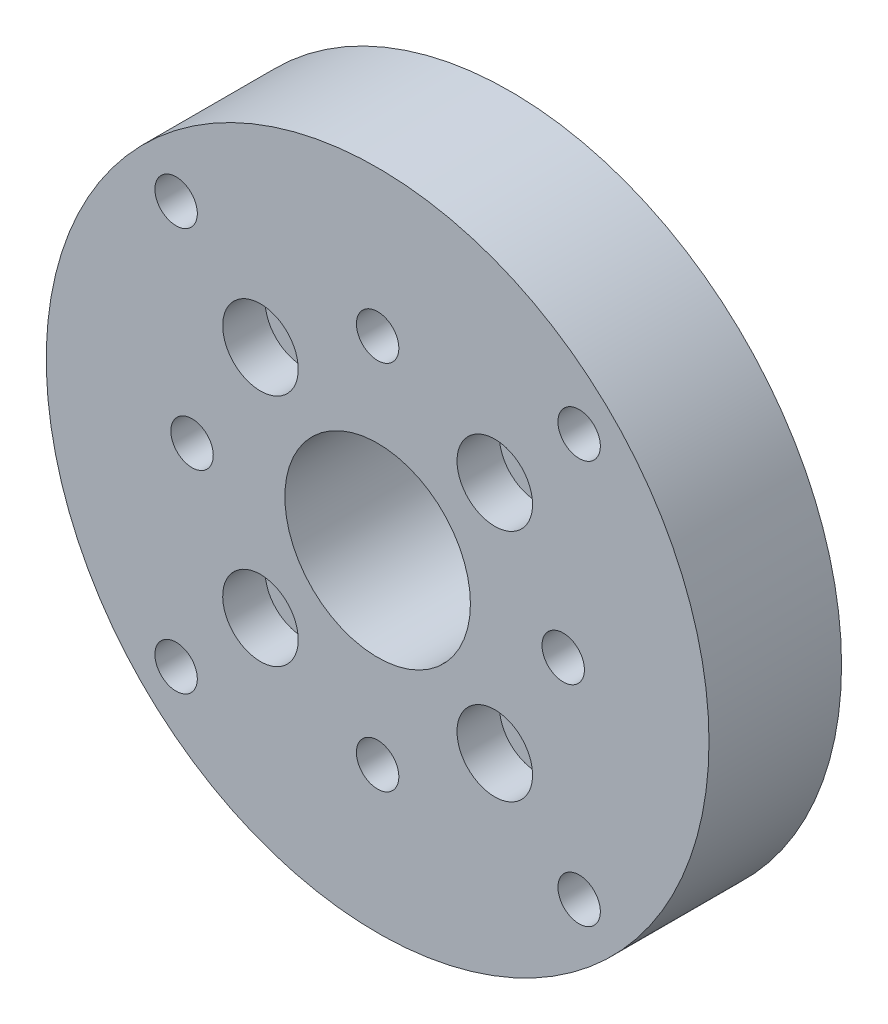
SolidWorks part; units mm, degrees
ref_plane "Front Plane" through (0, 0, 0) normal (0, 0, 1) x (1, 0, 0)
ref_plane "Top Plane" through (0, 0, 0) normal (0, 1, 0) x (1, 0, 0)
ref_plane "Right Plane" through (0, 0, 0) normal (1, 0, 0) x (0, 0, -1)
sketch "Sketch1" plane through (0, 0, 0) normal (0, 0, 1) x (1, 0, 0)
  circle A0 centre (0, 0) radius 25
  dimension "D1" = 50
extrude "Boss-Extrude1" add sketch "Sketch1" along normal blind 10
sketch "Sketch2" plane through (0, 0, 10) normal (0, 0, 1) x (1, 0, 0)
  line L0 (-8.8388, 8.8388) -> (0, 0) construction
  line L1 (0, 0) -> (0, 12.5) construction
  circle A0 centre (0, 0) radius 12.5 construction
  circle A1 centre (-8.8388, 8.8388) radius 1.6
  dimension "D1" = 25
  dimension "D2" = 3.2
  dimension "D3" = 45
extrude "Cut-Extrude1" cut sketch "Sketch2" against normal through all
sketch "Sketch5" plane through (0, 0, 10) normal (0, 0, 1) x (1, 0, 0)
  circle A0 centre (-8.8388, 8.8388) radius 1.6 construction
  circle A1 centre (-8.8388, 8.8388) radius 1.6 construction
  circle A2 centre (-8.8388, 8.8388) radius 2.85
  dimension "D1" = 5.7
extrude "Cut-Extrude4" cut sketch "Sketch5" against normal blind 3.2
pattern_circular "CirPattern1" count 4 over 360 about axis through (0, 0, 0) along (0, 0, 1) of "Cut-Extrude1", "Cut-Extrude4"
sketch "Sketch8" plane through (0, 0, 0) normal (0, 0, -1) x (-1, 0, 0)
  circle A0 centre (0, 0) radius 14 construction
  circle A1 centre (0, 14) radius 1.6
  dimension "D1" = 28
  dimension "D2" = 3.2
extrude "Cut-Extrude6" cut sketch "Sketch8" against normal through all
sketch "Sketch3" plane through (0, 0, 0) normal (0, 0, 1) x (1, 0, 0)
  line L1 (2.85, 12.3546) -> (2.85, 15.6454)
  line L2 (2.85, 15.6454) -> (0, 17.2909)
  line L3 (0, 17.2909) -> (-2.85, 15.6454)
  line L4 (-2.85, 15.6454) -> (-2.85, 12.3546)
  line L5 (-2.85, 12.3546) -> (0, 10.7091)
  line L6 (0, 10.7091) -> (2.85, 12.3546)
  circle A0 centre (0, 0) radius 14 construction
  circle A2 centre (0, 14) radius 2.85 construction
  point P4 (0, 0)
  point P12 (0, 0)
  point P13 (0.6758, 11.3365)
  dimension "D1" = 28
  dimension "D2" = 5.7
extrude "Cut-Extrude2" cut sketch "Sketch3" along normal blind 2.6
pattern_circular "CirPattern2" count 4 over 360 about axis through (0, 0, 0) along (0, 0, 1) of "Cut-Extrude2", "Cut-Extrude6"
sketch "Sketch4" plane through (0, 0, 10) normal (0, 0, 1) x (1, 0, 0)
  circle A0 centre (0, 0) radius 7
  dimension "D1" = 14
extrude "Cut-Extrude3" cut sketch "Sketch4" against normal through all
sketch "Sketch6" plane through (0, 0, 0) normal (0, 0, -1) x (-1, 0, 0)
  line L0 (15.2028, 15.2028) -> (0, 0) construction
  line L1 (0, 21.5) -> (0, 0) construction
  circle A0 centre (0, 0) radius 21.5 construction
  circle A1 centre (15.2028, 15.2028) radius 1.6
  dimension "D1" = 43
  dimension "D2" = 45
  dimension "D3" = 3.2
extrude "Cut-Extrude5" cut sketch "Sketch6" against normal through all
pattern_circular "CirPattern3" count 4 over 360 about axis through (0, 0, 0) along (0, 0, 1) of "Cut-Extrude5"
